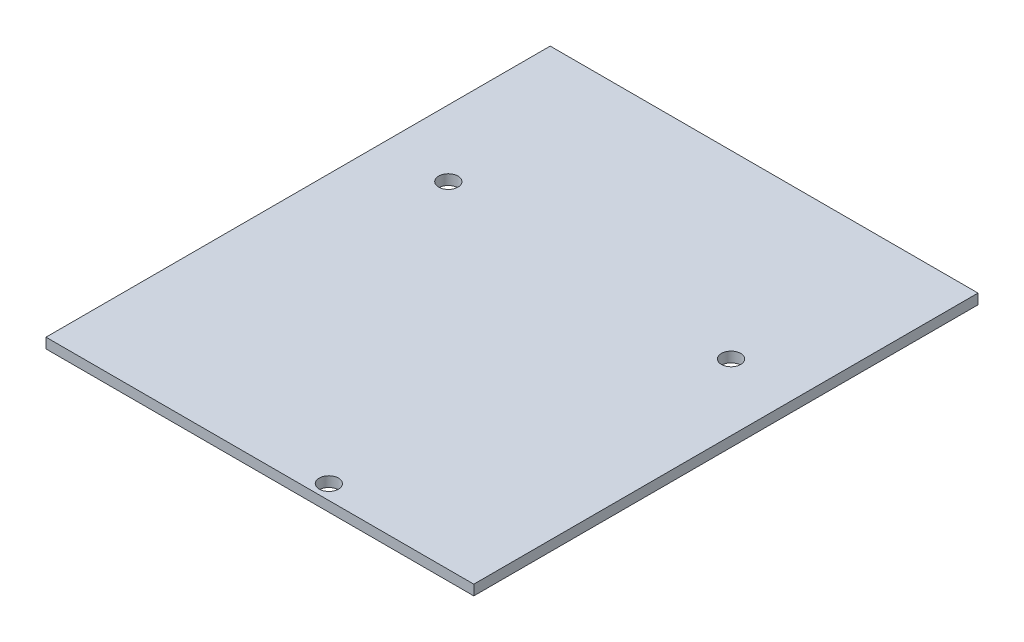
SolidWorks part; units mm, degrees
ref_plane "Front Plane" through (0, 0, 0) normal (0, 0, 1) x (1, 0, 0)
ref_plane "Top Plane" through (0, 0, 0) normal (0, 1, 0) x (1, 0, 0)
ref_plane "Right Plane" through (0, 0, 0) normal (1, 0, 0) x (0, 0, -1)
sketch "Sketch1" plane through (0, 0, 0) normal (0, 1, 0) x (1, 0, 0)
  line L1 (-30.7544, 33.3432) -> (39.2456, 33.3432)
  line L2 (-30.7544, 33.3432) -> (-30.7544, -49.1568)
  line L3 (-30.7544, -49.1568) -> (39.2456, -49.1568)
  line L4 (39.2456, 33.3432) -> (39.2456, -49.1568)
  circle A0 centre (13.1356, -46.7668) radius 1.575
  circle A1 centre (-19.8844, 5.8032) radius 1.575
  circle A2 centre (28.3756, 3.8032) radius 1.575
  dimension "D3" = 3.15
  dimension "D1" = 70
  dimension "D2" = 82.5
  dimension "D4" = 10.87
  dimension "D5" = 10.87
  dimension "D6" = 33.02
  dimension "D7" = 29.54
  dimension "D8" = 27.54
  dimension "D9" = 2.39
extrude "Boss-Extrude1" add sketch "Sketch1" along normal blind 1.67
